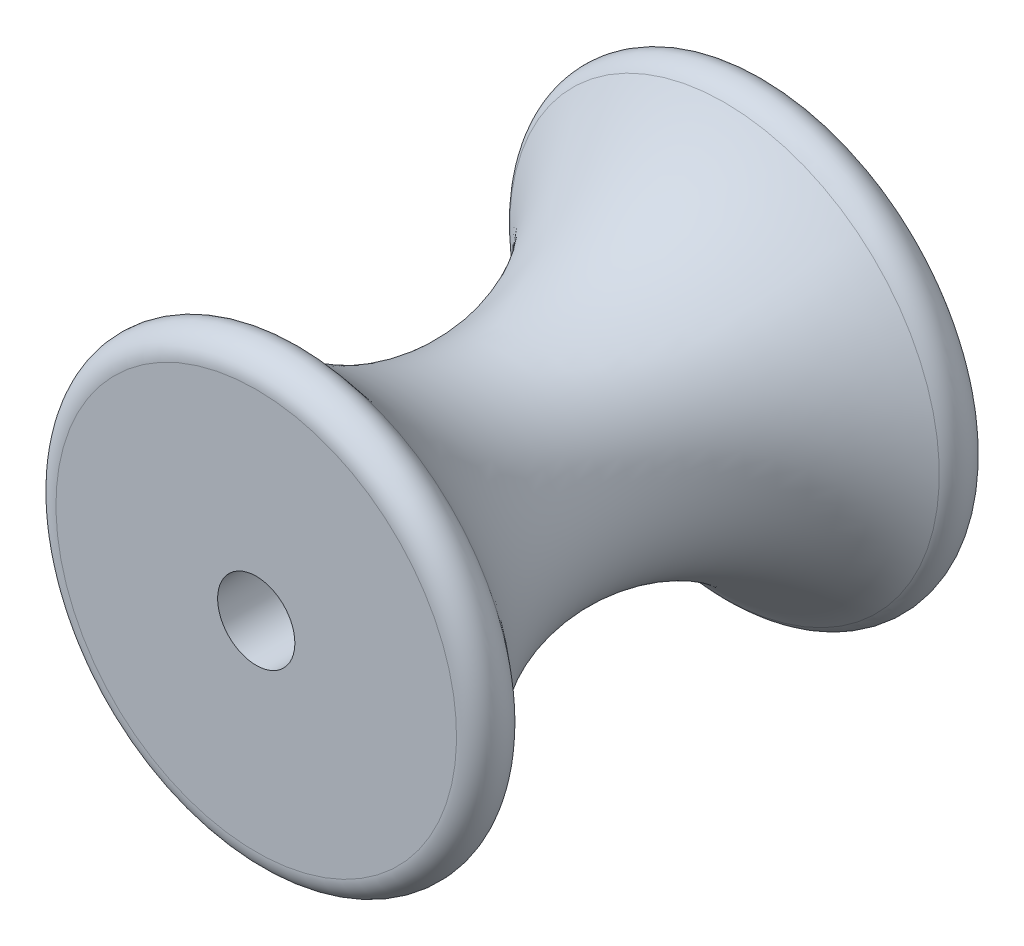
SolidWorks part; units mm, degrees
ref_plane "Front Plane" through (0, 0, 0) normal (0, 0, 1) x (1, 0, 0)
ref_plane "Top Plane" through (0, 0, 0) normal (0, 1, 0) x (1, 0, 0)
ref_plane "Right Plane" through (0, 0, 0) normal (1, 0, 0) x (0, 0, -1)
sketch "Sketch1" plane through (0, 0, 0) normal (1, 0, 0) x (0, 0, -1)
  line L0 (11, 0) -> (-11, 0) construction
  line L2 (11, 1.6) -> (-11, 1.6) construction
  line L4 (0, 55) -> (0, -55) construction
  line L5 (11, 1.6) -> (11, 15.5) construction
  line L6 (-11, 1.6) -> (-11, 15.5) construction
  line L7 (10.6, 1.6) -> (10.6, 12.5606)
  line L8 (-10.6, 1.6) -> (-10.6, 12.5606)
  line L9 (10.6, 1.6) -> (-10.6, 1.6)
  line L10 (11, 0) -> (11, 15.5965) construction
  circle A0 centre (0, 15.5) radius 11 construction
  arc A1 (10.6, 12.5606) -> (-10.6, 12.5606) centre (0, 15.5) cw
  point P2 (0, 0)
  dimension "D1" = 0.8
revolve "Revolve1" add sketch "Sketch1" angle 360 about L0
fillet "Fillet1" radius 1 2 edges at (0, 12.5606, 10.6) (0, 12.5606, -10.6)
